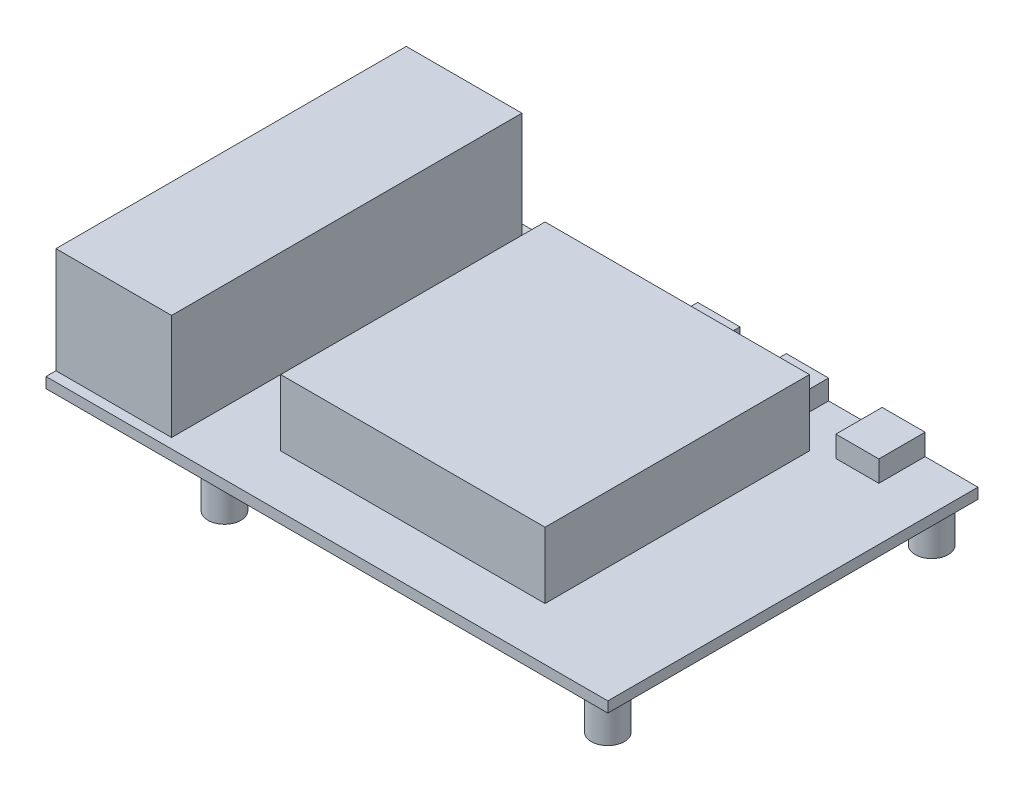
SolidWorks part; units mm, degrees
ref_plane "Front Plane" through (0, 0, 0) normal (0, 0, 1) x (1, 0, 0)
ref_plane "Top Plane" through (0, 0, 0) normal (0, 1, 0) x (1, 0, 0)
ref_plane "Right Plane" through (0, 0, 0) normal (1, 0, 0) x (0, 0, -1)
sketch "SK_P01_Standoff" plane through (0, 0, 0) normal (0, 1, 0) x (1, 0, 0)
  circle A0 centre (-19, 24.5) radius 2.5
extrude "P01_Standoff" add sketch "SK_P01_Standoff" along normal blind 6
sketch "SK_P02_Standoff" plane through (0, 0, 0) normal (0, 1, 0) x (1, 0, 0)
  circle A0 centre (-19, -24.5) radius 2.5
extrude "P02_Standoff" add sketch "SK_P02_Standoff" along normal blind 6
sketch "SK_P03_Standoff" plane through (0, 0, 0) normal (0, 1, 0) x (1, 0, 0)
  circle A0 centre (39, 24.5) radius 2.5
extrude "P03_Standoff" add sketch "SK_P03_Standoff" along normal blind 6
sketch "SK_P04_Standoff" plane through (0, 0, 0) normal (0, 1, 0) x (1, 0, 0)
  circle A0 centre (39, -24.5) radius 2.5
extrude "P04_Standoff" add sketch "SK_P04_Standoff" along normal blind 6
sketch "SK_P05_Board" plane through (0, 0, 0) normal (0, 1, 0) x (1, 0, 0)
  line L0 (-42.5, -28) -> (42.5, -28)
  line L1 (42.5, -28) -> (42.5, 28)
  line L2 (42.5, 28) -> (-42.5, 28)
  line L3 (-42.5, 28) -> (-42.5, -28)
extrude "P05_Board" add sketch "SK_P05_Board" along normal blind 1.6 from offset 6
sketch "SK_P06_Activecooler" plane through (0, 0, 0) normal (0, 1, 0) x (1, 0, 0)
  line L0 (-15, -20) -> (25, -20)
  line L1 (25, -20) -> (25, 20)
  line L2 (25, 20) -> (-15, 20)
  line L3 (-15, 20) -> (-15, -20)
extrude "P06_Activecooler" add sketch "SK_P06_Activecooler" along normal blind 10 from offset 7.6
sketch "SK_P07_USBandEthernet" plane through (0, 0, 0) normal (0, 1, 0) x (1, 0, 0)
  line L0 (-42.5, -26.5) -> (-25, -26.5)
  line L1 (-25, -26.5) -> (-25, 26.5)
  line L2 (-25, 26.5) -> (-42.5, 26.5)
  line L3 (-42.5, 26.5) -> (-42.5, -26.5)
extrude "P07_USBandEthernet" add sketch "SK_P07_USBandEthernet" along normal blind 16 from offset 7.6
sketch "SK_P08_USBCpower" plane through (0, 0, 0) normal (0, 1, 0) x (1, 0, 0)
  line L0 (28, 21) -> (34.5, 21)
  line L1 (34.5, 21) -> (34.5, 28)
  line L2 (34.5, 28) -> (28, 28)
  line L3 (28, 28) -> (28, 21)
extrude "P08_USBCpower" add sketch "SK_P08_USBCpower" along normal blind 3.2 from offset 7.6
sketch "SK_P09_microHDMI0" plane through (0, 0, 0) normal (0, 1, 0) x (1, 0, 0)
  line L0 (13.5, 21) -> (19.9, 21)
  line L1 (19.9, 21) -> (19.9, 28)
  line L2 (19.9, 28) -> (13.5, 28)
  line L3 (13.5, 28) -> (13.5, 21)
extrude "P09_microHDMI0" add sketch "SK_P09_microHDMI0" along normal blind 3 from offset 7.6
sketch "SK_P10_microHDMI1" plane through (0, 0, 0) normal (0, 1, 0) x (1, 0, 0)
  line L0 (0.1, 21) -> (6.5, 21)
  line L1 (6.5, 21) -> (6.5, 28)
  line L2 (6.5, 28) -> (0.1, 28)
  line L3 (0.1, 28) -> (0.1, 21)
extrude "P10_microHDMI1" add sketch "SK_P10_microHDMI1" along normal blind 3 from offset 7.6
